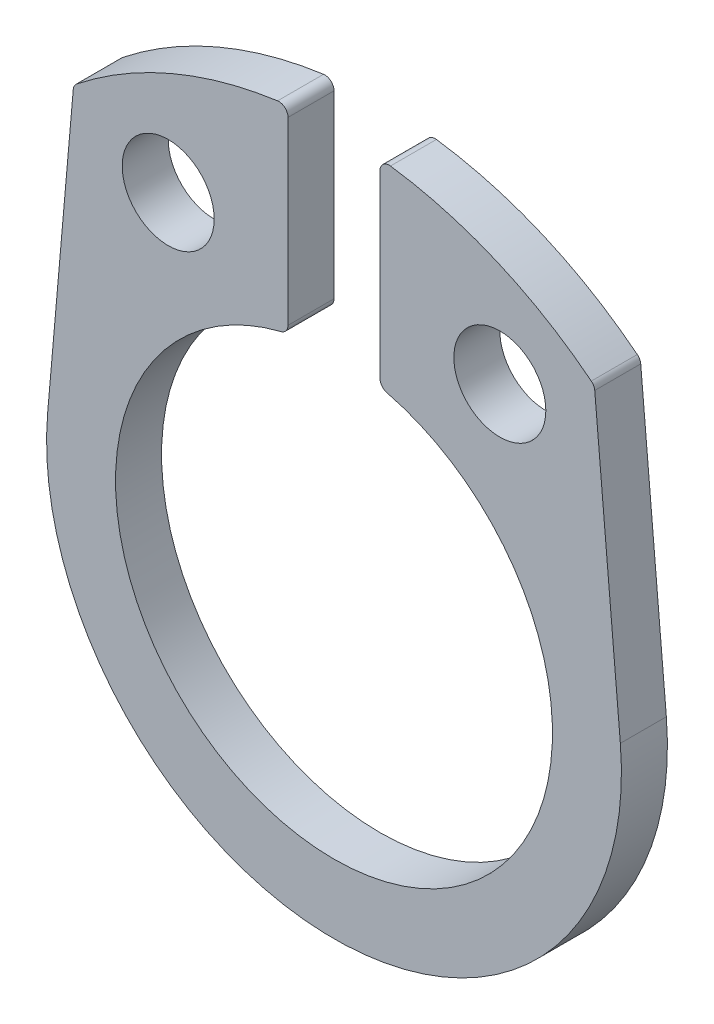
SolidWorks part; units mm, degrees
ref_plane "Frente" through (0, 0, 0) normal (0, 0, 1) x (1, 0, 0)
ref_plane "Topo" through (0, 0, 0) normal (0, 1, 0) x (1, 0, 0)
ref_plane "Lateral" through (0, 0, 0) normal (1, 0, 0) x (0, 0, -1)
sketch "Sketch1" plane through (0, 0, 0) normal (0, 0, 1) x (1, 0, 0)
  line L0 (-5.6618, 6.996) -> (-6.2262, 0.5447)
  line L2 (6.2262, 0.5447) -> (5.6618, 6.996)
  line L4 (0, 9) -> (0, 0) construction
  line L7 (-1, 8.9443) -> (-1, 4.6435)
  line L8 (-1, 4.6435) -> (1, 4.6435) construction
  line L9 (1, 8.9443) -> (1, 4.6435)
  arc A0 (-1, 4.6435) -> (1, 4.6435) centre (0, 0) ccw
  arc A1 (-6.2262, 0.5447) -> (6.2262, 0.5447) centre (0, 0) ccw
  arc A2 (5.6618, 6.996) -> (1, 8.9443) centre (0, 0) ccw
  arc A3 (-1, 8.9443) -> (-5.6618, 6.996) centre (0, 0) ccw
  point P7 (-1.8093, 4.4459)
  point P15 (0.4536, 4.5441)
  dimension "D1" = 9.5
  dimension "D2" = 1.5
  dimension "D3" = 18
  dimension "D4" = 10
  dimension "D5" = 5
  dimension "D6" = 2
extrude "Boss-Extrude1" add sketch "Sketch1" along normal mid plane 1
sketch "Sketch2" plane through (0, 0, 0.5) normal (0, 0, 1) x (1, 0, 0)
  line L0 (-3.6056, 6) -> (0, 6) construction
  line L1 (0, 6) -> (3.6056, 6) construction
  line L2 (0, 6) -> (0, 0) construction
  circle A0 centre (0, 0) radius 7 construction
  circle A1 centre (-3.6056, 6) radius 1
  circle A2 centre (3.6056, 6) radius 1
  dimension "D2" = 14
  dimension "D3" = 2
  dimension "D1" = 6
extrude "Cut-Extrude1" cut sketch "Sketch2" against normal through all
fillet "Fillet1" radius 0.2 6 edges at (1, 4.6435, 0) (5.6618, 6.996, 0) (1, 8.9443, 0) (-1, 8.9443, 0) (-1, 4.6435, 0) (-5.6618, 6.996, 0)
